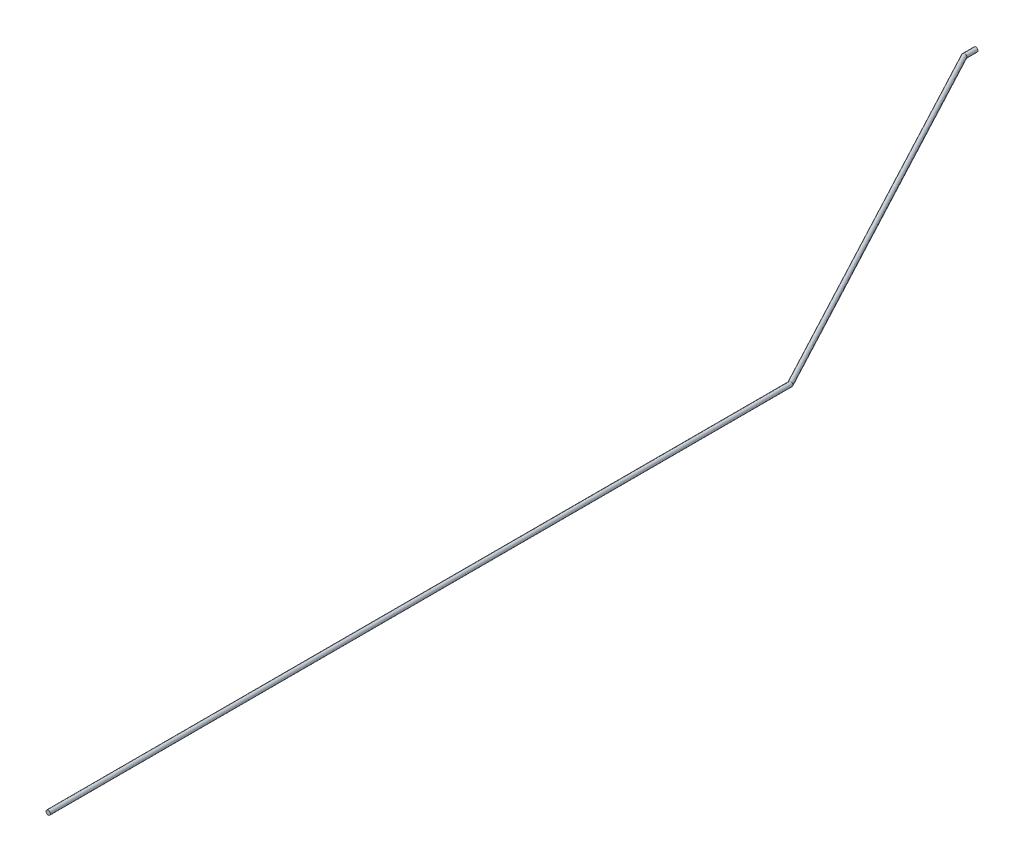
SolidWorks part; units mm, degrees
ref_plane "Front Plane" through (0, 0, 0) normal (0, 0, 1) x (1, 0, 0)
ref_plane "Top Plane" through (0, 0, 0) normal (0, 1, 0) x (1, 0, 0)
ref_plane "Right Plane" through (0, 0, 0) normal (1, 0, 0) x (0, 0, -1)
sketch "Sketch1" plane through (0, 0, 0) normal (0, 1, 0) x (1, 0, 0)
  line L0 (0, 0) -> (0, 812.8)
  line L1 (0, 812.8) -> (-215.9, 1219.2) construction
  line L2 (-215.9, 1219.2) -> (0, 812.8)
  line L3 (-215.9, 1219.2) -> (-215.9, 1231.9)
  dimension "D3" = 1219.2
  dimension "D1" = 215.9
  dimension "D2" = 812.8
  dimension "D4" = 12.7
sketch "Sketch2" plane through (0, 0, 0) normal (0, 0, 1) x (1, 0, 0)
  circle A0 centre (0, 0) radius 2.3813
  dimension "D1" = 4.7625
sweep "Sweep1" add profiles "Sketch2" path "Sketch1"
